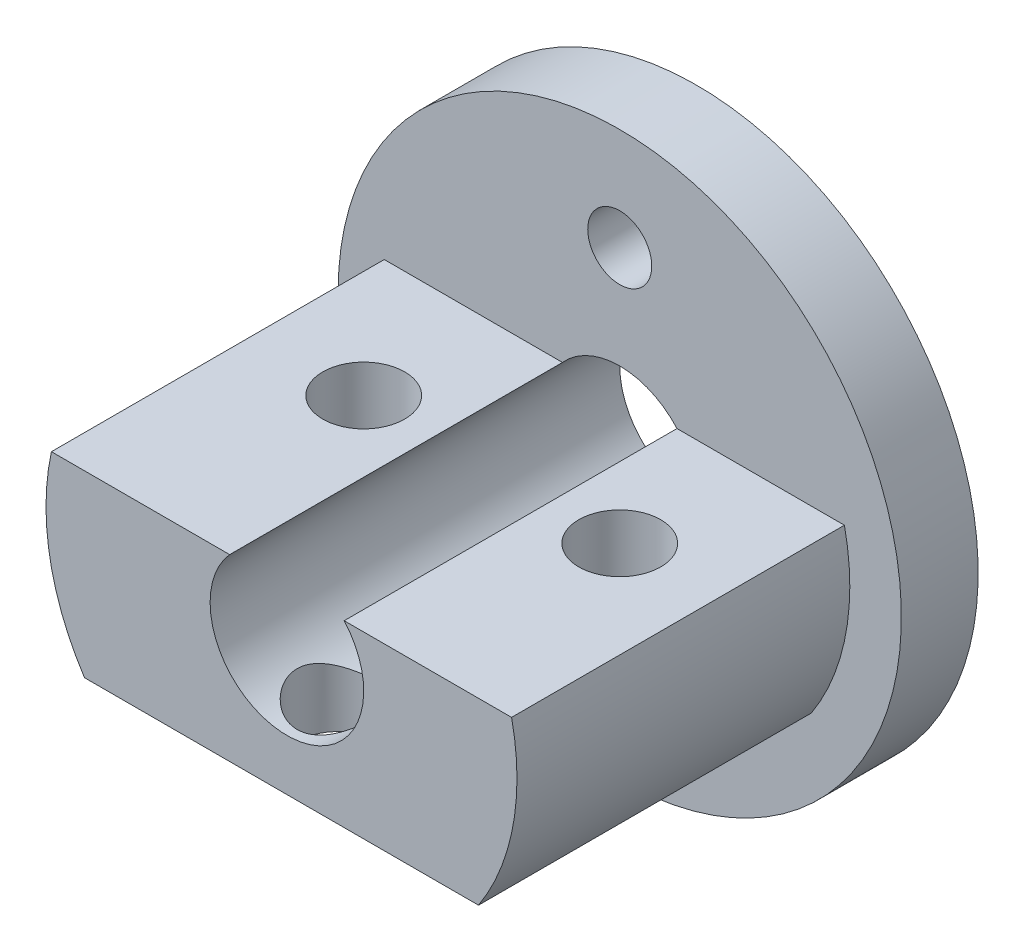
SolidWorks part; units mm, degrees
material "1060 合金"
ref_plane "前视基准面" through (0, 0, 0) normal (0, 0, 1) x (1, 0, 0)
ref_plane "上视基准面" through (0, 0, 0) normal (0, 1, 0) x (1, 0, 0)
ref_plane "右视基准面" through (0, 0, 0) normal (1, 0, 0) x (0, 0, -1)
ref_plane "基准面4" through (0, 0, 0) normal (0, -1, 0) x (1, 0, 0)
sketch "草图1" plane through (0, 0, 0) normal (0, -1, 0) x (1, 0, 0)
  line L0 (11, 3) -> (0, 3)
  line L1 (0, 3) -> (0, 0)
  line L2 (0, 0) -> (11, 0)
  line L3 (11, 0) -> (11, 3)
  line L4 (0, 3) -> (0, 0) construction
revolve "旋转1" add sketch "草图1" angle 360 about L4
sketch "草图2" plane through (0, 0, 3) normal (0, 0, 1) x (1, 0, 0)
  line L0 (7.4833, -5) -> (-7.9071, -5)
  line L1 (-9.1988, 2) -> (8.775, 2)
  arc A0 (-7.9071, -5) -> (-9.1988, 2) centre (-0.2119, 0.0391) cw
  arc A1 (8.775, 2) -> (7.4833, -5) centre (-0.2119, 0.0391) cw
extrude "凸台-拉伸1" add sketch "草图2" along normal blind 13
hole_wizard "Ø2.5 (2.5) 直径孔1" positions "草图4" profile "草图3" hole size "Ø2.5" standard "ANSI Metric"
sketch "草图4" plane through (0, 0, 0) normal (0, 0, -1) x (-1, 0, 0)
  point P0 (0, -7)
  point P1 (0, 7)
sketch "草图3" plane through (0, -7, 0) normal (1, 0, 0) x (0, 1, 0)
  line L0 (0, 0) -> (0, 16)
  line L1 (0, 16) -> (1.25, 16)
  line L2 (1.25, 16) -> (1.25, 0)
  line L5 (1.25, 0) -> (0, 0)
  line L11 (0, -6.35) -> (0, 107.95) construction
  dimension "通孔孔直径" = 2.5
  dimension "通孔孔深度" = 16
hole_wizard "Ø3.2 (3.2) 直径孔1" positions "草图6" profile "草图5" hole size "Ø3.2" standard "ANSI Metric"
sketch "草图6" plane through (0, -5, 0) normal (0, -1, 0) x (-1, 0, 0)
  point P0 (5, -8)
  point P1 (-5, -8)
sketch "草图5" plane through (-5, -5, 8) normal (1, 0, 0) x (0, 0, -1)
  line L0 (0, 0) -> (0, 16)
  line L1 (0, 16) -> (1.6, 16)
  line L2 (1.6, 16) -> (1.6, 0)
  line L5 (1.6, 0) -> (0, 0)
  line L11 (0, -6.35) -> (0, 107.95) construction
  dimension "通孔孔直径" = 3.2
  dimension "通孔孔深度" = 16
hole_wizard "Ø6.0 (6) 直径孔1" positions "草图8" profile "草图7" hole size "Ø6.0" standard "ANSI Metric"
sketch "草图8" plane through (0, 0, 0) normal (0, 0, -1) x (-1, 0, 0)
  point P0 (0, 0)
sketch "草图7" plane through (0, 0, 0) normal (1, 0, 0) x (0, 1, 0)
  line L0 (0, 0) -> (0, 16)
  line L1 (0, 16) -> (3, 16)
  line L2 (3, 16) -> (3, 0)
  line L5 (3, 0) -> (0, 0)
  line L11 (0, -6.35) -> (0, 107.95) construction
  dimension "通孔孔直径" = 6
  dimension "通孔孔深度" = 16
hole_wizard "Ø3.2 (3.2) 直径孔2" positions "草图10" profile "草图9" hole size "Ø3.2" standard "ANSI Metric"
sketch "草图10" plane through (0, -5, 0) normal (0, -1, 0) x (-1, 0, 0)
  point P0 (0, -14)
sketch "草图9" plane through (0, -5, 14) normal (1, 0, 0) x (0, 0, -1)
  line L0 (0, 0) -> (0, 16)
  line L1 (0, 16) -> (1.6, 16)
  line L2 (1.6, 16) -> (1.6, 0)
  line L5 (1.6, 0) -> (0, 0)
  line L11 (0, -6.35) -> (0, 107.95) construction
  dimension "通孔孔直径" = 3.2
  dimension "通孔孔深度" = 16
